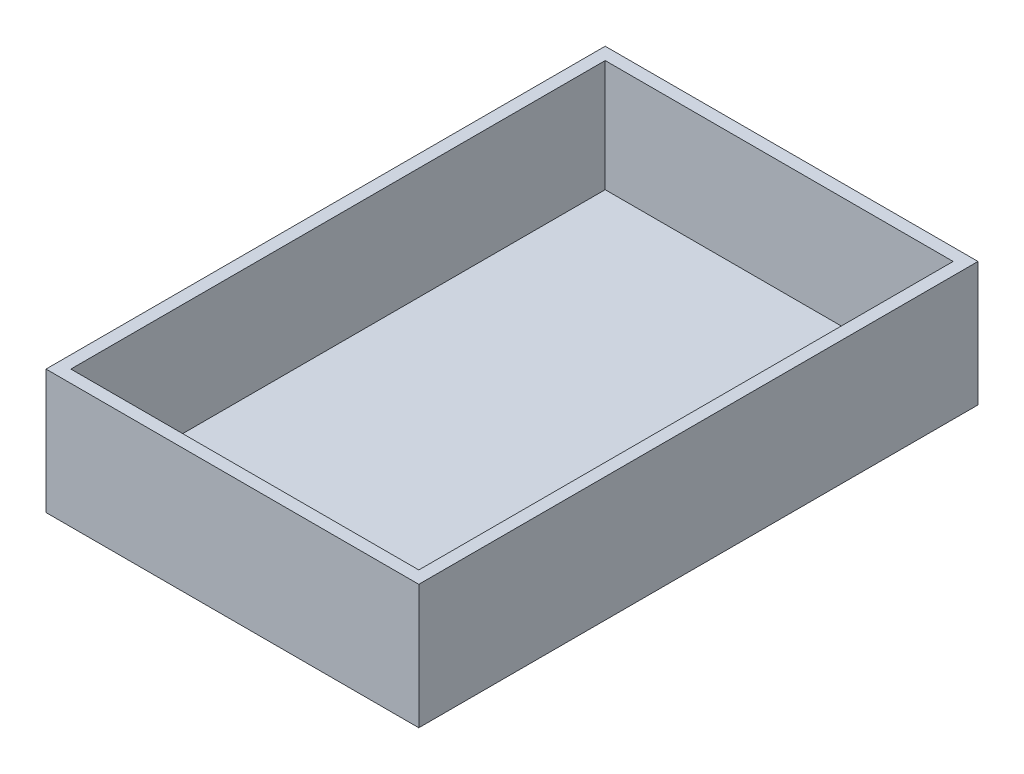
SolidWorks part; units mm, degrees
material "Pino"
ref_plane "Alzado" through (0, 0, 0) normal (0, 0, 1) x (1, 0, 0)
ref_plane "Planta" through (0, 0, 0) normal (0, 1, 0) x (1, 0, 0)
ref_plane "Vista lateral" through (0, 0, 0) normal (1, 0, 0) x (0, 0, -1)
sketch "Croquis1" plane through (0, 0, 0) normal (0, 0, 1) x (1, 0, 0)
  line L1 (0, 0) -> (300, 0)
  line L2 (0, 0) -> (0, 100)
  line L3 (0, 100) -> (300, 100)
  line L4 (300, 0) -> (300, 100)
  dimension "D1" = 300
  dimension "D2" = 100
extrude "Saliente-Extruir1" add sketch "Croquis1" against normal blind 450
sketch "Croquis2" plane through (0, 100, 0) normal (0, 1, 0) x (1, 0, 0)
  line L0 (0, 450) -> (0, 0) construction
  line L1 (10, 10) -> (290, 10)
  line L2 (10, 10) -> (10, 440)
  line L3 (10, 440) -> (290, 440)
  line L4 (290, 10) -> (290, 440)
  line L5 (300, 450) -> (0, 450) construction
  line L6 (300, 450) -> (300, 0) construction
  line L7 (300, 0) -> (0, 0) construction
  dimension "D1" = 10
  dimension "D2" = 10
  dimension "D3" = 10
  dimension "D4" = 10
extrude "Cortar-Extruir1" cut sketch "Croquis2" against normal blind 90
